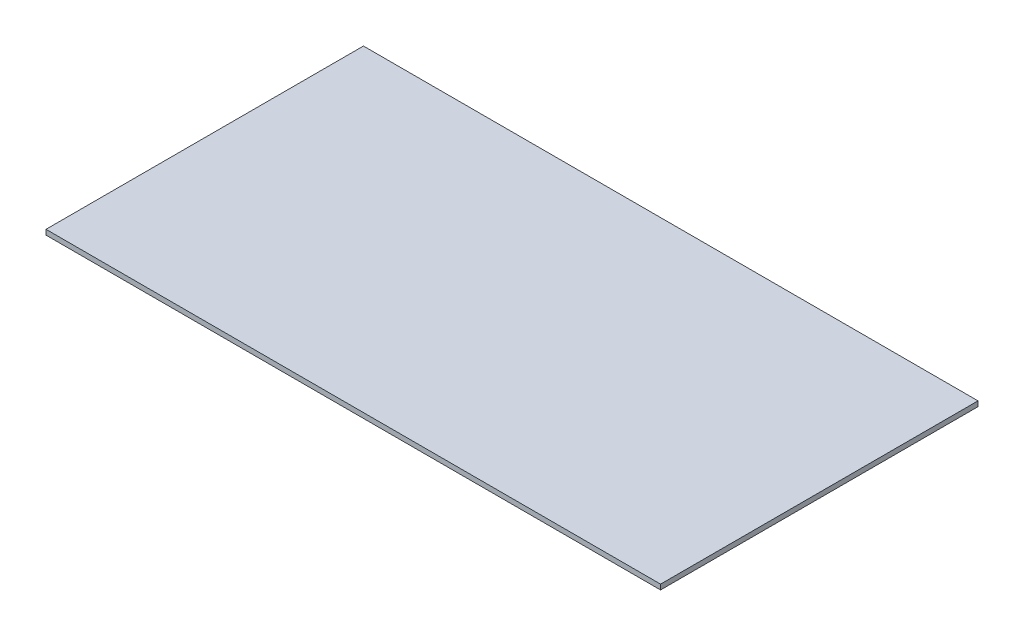
SolidWorks part; units mm, degrees
ref_plane "Front Plane" through (0, 0, 0) normal (0, 0, 1) x (1, 0, 0)
ref_plane "Top Plane" through (0, 0, 0) normal (0, 1, 0) x (1, 0, 0)
ref_plane "Right Plane" through (0, 0, 0) normal (1, 0, 0) x (0, 0, -1)
sketch "Sketch1" plane through (0, 0, 0) normal (0, 1, 0) x (1, 0, 0)
  line L1 (0, 0) -> (242, 0)
  line L2 (0, 0) -> (0, 125)
  line L3 (0, 125) -> (242, 125)
  line L4 (242, 0) -> (242, 125)
  dimension "D1" = 242
  dimension "D2" = 125
extrude "Boss-Extrude1" add sketch "Sketch1" along normal blind 2
